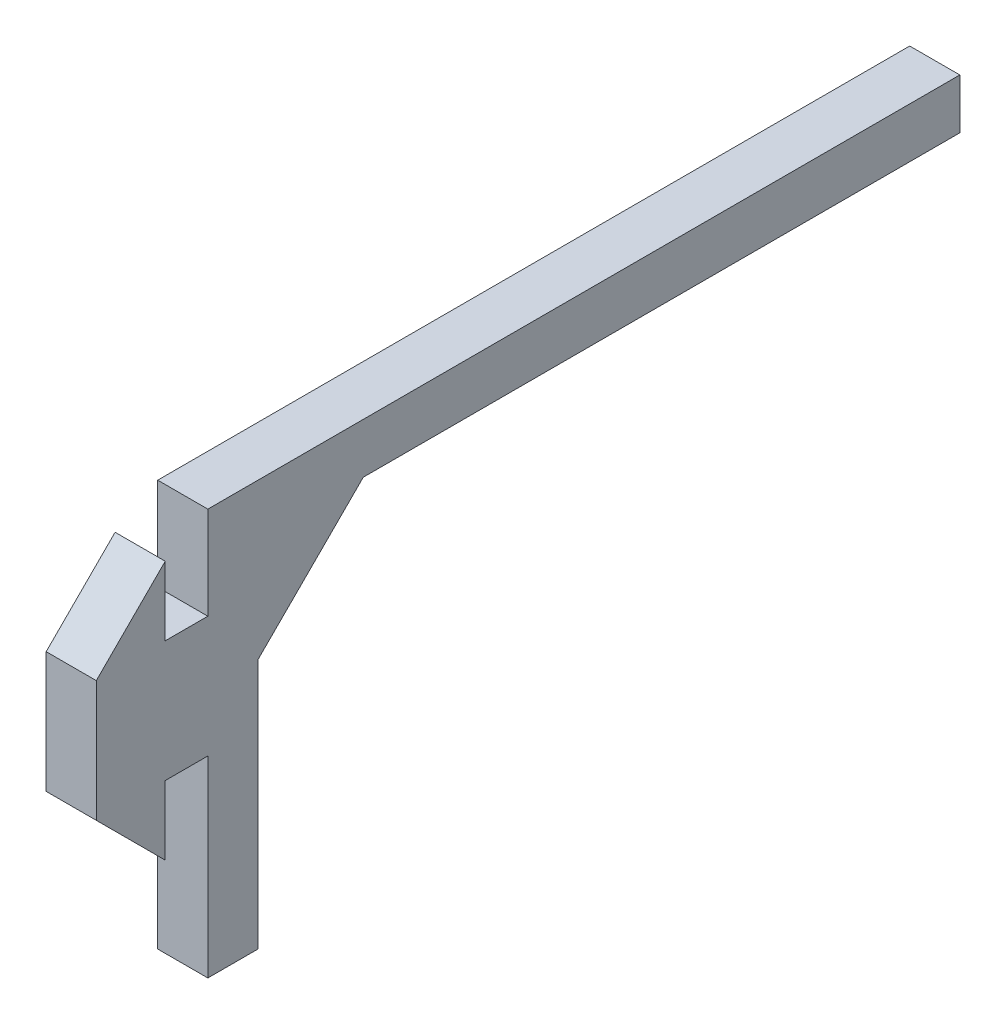
SolidWorks part; units mm, degrees
ref_plane "Front Plane" through (0, 0, 0) normal (0, 0, 1) x (1, 0, 0)
ref_plane "Top Plane" through (0, 0, 0) normal (0, 1, 0) x (1, 0, 0)
ref_plane "Right Plane" through (0, 0, 0) normal (1, 0, 0) x (0, 0, -1)
sketch "Sketch1" plane through (0, 0, 0) normal (1, 0, 0) x (0, 0, -1)
  line L0 (0, 0) -> (0, 20)
  line L1 (0, 20) -> (30, 20)
  line L2 (30, 20) -> (30, 19.9)
  line L3 (2, 0) -> (2, 14.2)
  line L4 (2, 16.2) -> (0, 16.2)
  line L5 (2, 0) -> (0, 0)
  line L6 (0, 10) -> (2, 10) construction
  line L7 (0, 10) -> (-1.7, 10) construction
  line L8 (30, 19.9) -> (2, 19.9)
  line L9 (2, 19.9) -> (2, 16.2)
  line L10 (2, 16.2) -> (30, 16.2)
  line L11 (30, 16.2) -> (30, 14.2)
  line L12 (30, 14.2) -> (2, 14.2)
  line L13 (-1.7, 10) -> (-1.7, 12.5) construction
  line L14 (-1.7, 12.5) -> (-1.7, 15.25)
  line L15 (-1.7, 15.25) -> (-4.45, 12.5)
  line L16 (-1.7, 10) -> (-1.7, 7.6717) construction
  line L17 (-1.7, 7.6717) -> (-1.7, 4.9217)
  line L18 (-1.7, 4.9217) -> (-4.45, 7.6717)
  line L19 (-4.45, 12.5) -> (-4.45, 7.6717)
  line L20 (-1.7, 12.5) -> (0, 12.5)
  line L21 (-1.7, 7.6717) -> (0, 7.6717)
  line L22 (2, 10) -> (6.2, 14.2)
  dimension "D1" = 20
  dimension "D2" = 14.2
  dimension "D3" = 2
  dimension "D4" = 2
  dimension "D5" = 30
extrude "Boss-Extrude2" add sketch "Sketch1" along normal blind 2
